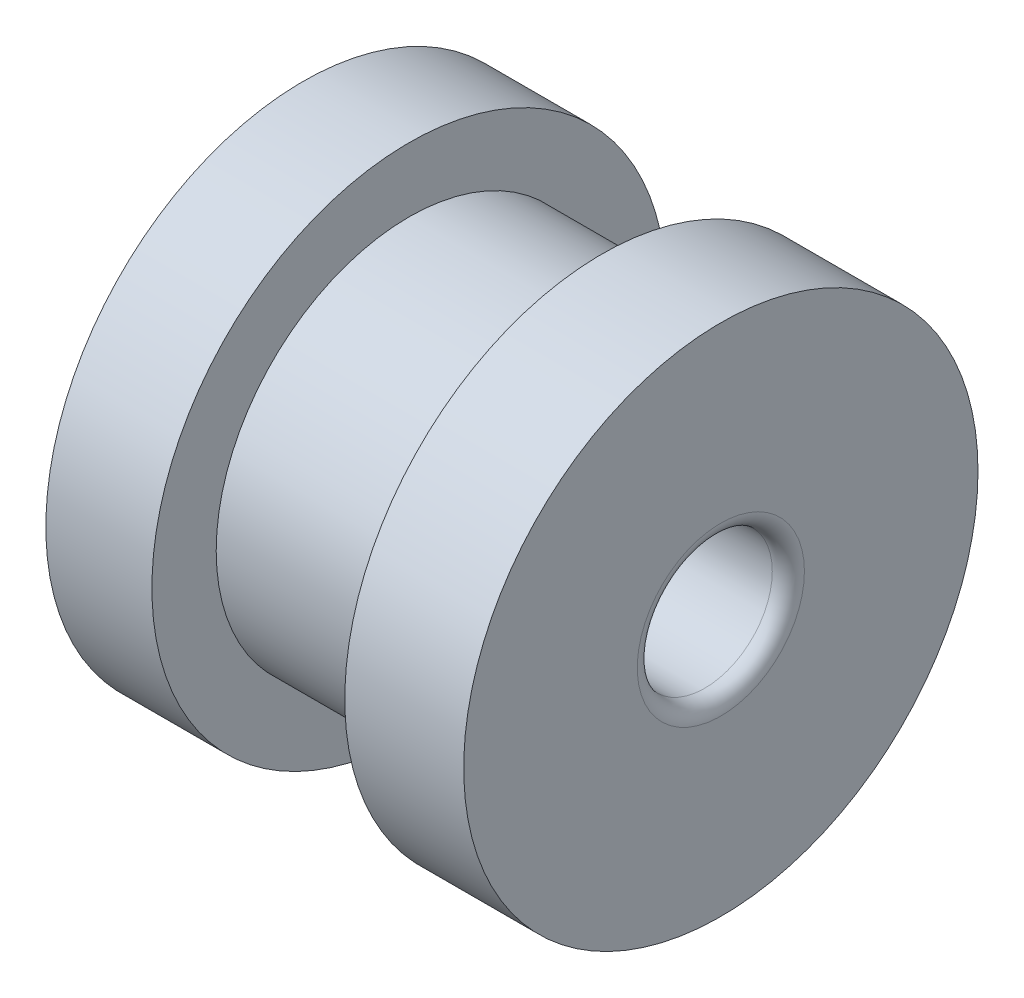
SolidWorks part; units mm, degrees
ref_plane "Front Plane" through (0, 0, 0) normal (0, 0, 1) x (1, 0, 0)
ref_plane "Top Plane" through (0, 0, 0) normal (0, 1, 0) x (1, 0, 0)
ref_plane "Right Plane" through (0, 0, 0) normal (1, 0, 0) x (0, 0, -1)
sketch "Sketch1" plane through (0, 0, 0) normal (1, 0, 0) x (0, 0, -1)
  circle A0 centre (0, 0) radius 8
  dimension "D1" = 16
extrude "Boss-Extrude1" add sketch "Sketch1" against normal blind 13
ref_axis "Axis1" through (-13, 0, 0) along (1, 0, 0)
sketch "Sketch4" plane through (0, 0, 0) normal (1, 0, 0) x (0, 0, -1)
  circle A0 centre (0, 0) radius 2.1
  dimension "D1" = 4.2
extrude "Cut-Extrude1" cut sketch "Sketch4" against normal through all
fillet "Fillet1" radius 0.5 2 edges at (0, 0, -2.1) (-13, 0, -2.1)
sketch "Sketch2" plane through (0, 0, 0) normal (0, 0, 1) x (1, 0, 0)
  line L0 (0, -8) -> (0, 8) construction
  line L1 (-9.7, 8) -> (-3.7, 8)
  line L2 (-9.7, 8) -> (-9.7, 6)
  line L3 (-9.7, 6) -> (-3.7, 6)
  line L4 (-3.7, 8) -> (-3.7, 6)
  line L5 (0, 8) -> (-13, 8) construction
  dimension "D1" = 3.7
  dimension "D2" = 6
  dimension "D3" = 2
revolve "Cut-Revolve1" cut sketch "Sketch2" angle 360 about axis through (-13, 0, 0) along (1, 0, 0)
